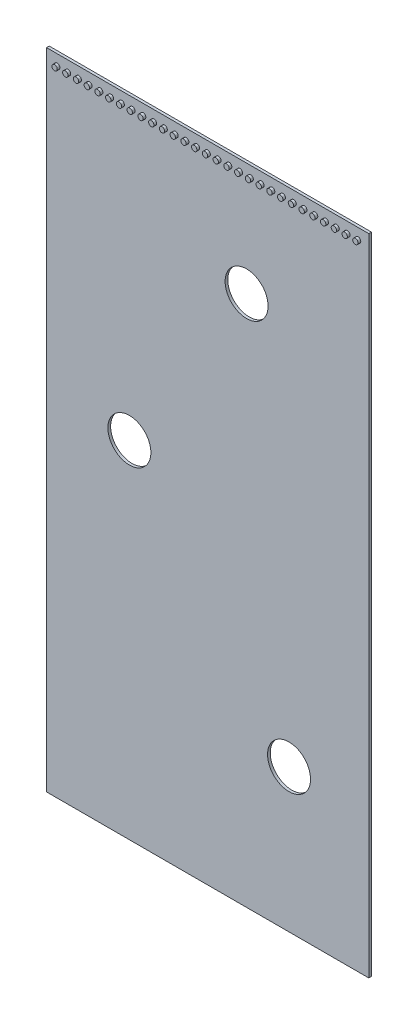
SolidWorks part; units mm, degrees
material "Pine"
ref_plane "Front Plane" through (0, 0, 0) normal (0, 0, 1) x (1, 0, 0)
ref_plane "Top Plane" through (0, 0, 0) normal (0, 1, 0) x (1, 0, 0)
ref_plane "Right Plane" through (0, 0, 0) normal (1, 0, 0) x (0, 0, -1)
sketch "Sketch1" plane through (0, 0, 0) normal (0, 0, 1) x (1, 0, 0)
  line L1 (0, 0) -> (762, 0)
  line L2 (0, 0) -> (0, 1524)
  line L3 (0, 1524) -> (762, 1524)
  line L4 (762, 0) -> (762, 1524)
  circle A0 centre (473.041, 1256.5172) radius 50.8
  circle A1 centre (195.9855, 818.0279) radius 50.8
  circle A2 centre (573.3918, 338.0893) radius 50.8
  point P11 (849.4744, 0)
  point P12 (1149.2313, 1524)
  point P13 (711.2151, 1150.7988)
  point P14 (361.4793, 774.5678)
  point P15 (523.0996, 1148.1492)
  point P16 (502.31, 236.8295)
  point P17 (222.0428, 709.4963)
  point P18 (540.6687, 1291.4219)
  point P19 (233.0717, 868.2033)
  point P20 (573.3918, 338.0893)
  point P21 (473.041, 1256.5172)
  point P22 (195.9855, 818.0279)
  dimension "D3" = 101.6
  dimension "D1" = 1524
  dimension "D2" = 762
extrude "Boss-Extrude1" add sketch "Sketch1" along normal blind 6.35
ref_plane "Plane1" through (0, 0, 3.175) normal (0, 0, 1) x (1, 0, 0)
sketch "Sketch3" plane through (0, 0, 3.175) normal (0, 0, 1) x (1, 0, 0)
  line L0 (0, 1524) -> (0, 0) construction
  line L1 (762, 1524) -> (0, 1524) construction
  circle A0 centre (25.4, 1498.6) radius 6.35
  dimension "D1" = 12.7
  dimension "D2" = 25.4
  dimension "D3" = 25.4
extrude "Boss-Extrude2" add sketch "Sketch3" along normal mid plane 19.05
pattern_linear "LPattern1" count 29 spacing 25.4 along (1, 0, 0) of "Boss-Extrude2"
